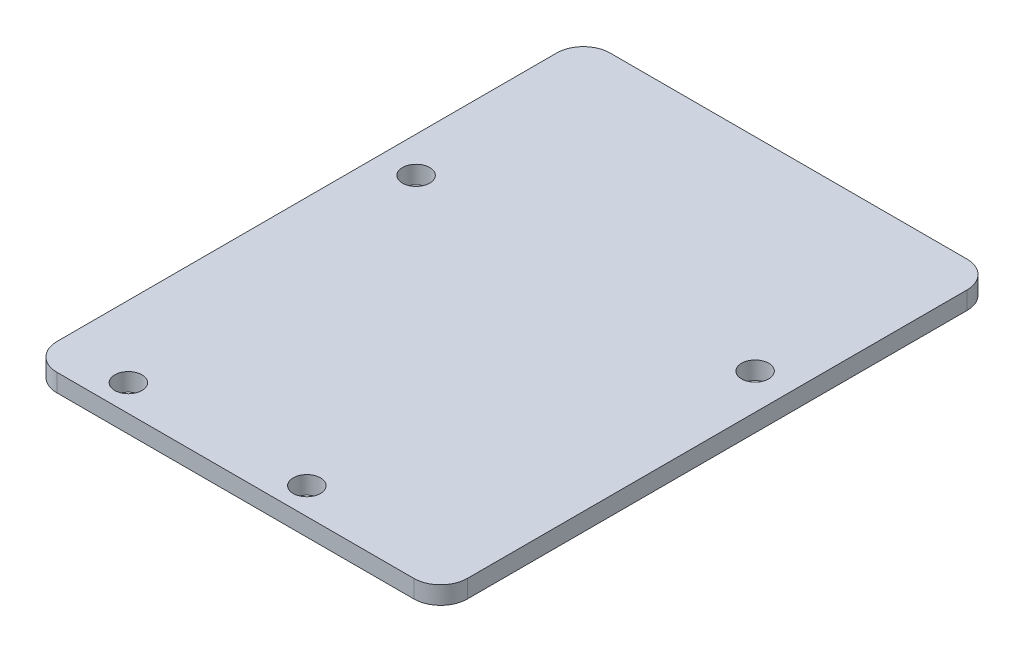
SolidWorks part; units mm, degrees
material "Thornel Mat VMA"
ref_plane "前视基准面" through (0, 0, 0) normal (0, 0, 1) x (1, 0, 0)
ref_plane "上视基准面" through (0, 0, 0) normal (0, 1, 0) x (1, 0, 0)
ref_plane "右视基准面" through (0, 0, 0) normal (1, 0, 0) x (0, 0, -1)
other "Configuration Table"
sketch "草图1" plane through (0, 0, 0) normal (0, 1, 0) x (1, 0, 0)
  line L1 (-23, -31) -> (23, -31)
  line L2 (-23, -31) -> (-23, 31)
  line L3 (-23, 31) -> (23, 31)
  line L4 (23, -31) -> (23, 31)
  line L5 (-23, -31) -> (23, 31) construction
  line L6 (-23, 31) -> (23, -31) construction
  point P0 (0, 0)
  dimension "D1" = 46
  dimension "D2" = 62
extrude "凸台-拉伸1" add sketch "草图1" along normal blind 2
sketch "草图2" plane through (0, 0, 0) normal (0, -1, 0) x (1, 0, 0)
  circle A0 centre (19, -8.25) radius 1.25 construction
  circle A1 centre (-19, -8.25) radius 1.25 construction
  circle A2 centre (19, -8.25) radius 1.25 construction
  circle A3 centre (-19, -8.25) radius 1.25 construction
  circle A4 centre (19, -8.25) radius 1.525
  circle A5 centre (-19, -8.25) radius 1.525
  dimension "D1" = 3.05
extrude "切除-拉伸1" cut sketch "草图2" against normal up to surface (2 mm away) up to face at (0, 2, 0)
sketch "草图3" plane through (0, 0, 0) normal (0, -1, 0) x (1, 0, 0)
  circle A0 centre (5, 28) radius 1.25 construction
  circle A1 centre (-15, 28) radius 1.25 construction
  circle A2 centre (5, 28) radius 1.25 construction
  circle A3 centre (-15, 28) radius 1.25 construction
  circle A4 centre (5, 28) radius 1.525
  circle A5 centre (-15, 28) radius 1.525
  dimension "D1" = 3.05
extrude "切除-拉伸2" cut sketch "草图3" against normal up to surface (2 mm away) up to face at (19, 2, -9.775)
fillet "圆角1" radius 3 4 edges at (-23, 1, -31) (23, 1, -31) (23, 1, 31) (-23, 1, 31)
